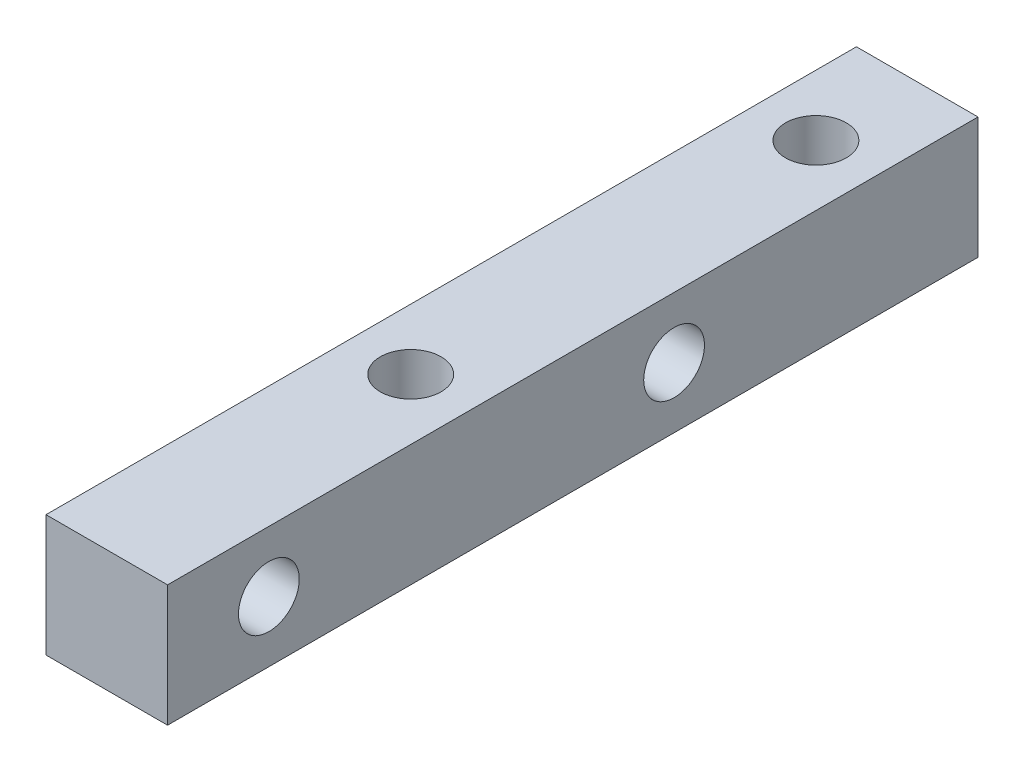
SolidWorks part; units mm, degrees
other "标注1"
sketch "草图4" plane through (6, 6, 0) normal (0.1455, 0.9686, -0.2015) x (-0.3057, 0.2377, 0.922)
material "6061-T6 (SS)"
ref_plane "前视基准面" through (0, 0, 0) normal (0, 0, 1) x (1, 0, 0)
ref_plane "上视基准面" through (0, 0, 0) normal (0, 1, 0) x (1, 0, 0)
ref_plane "右视基准面" through (0, 0, 0) normal (1, 0, 0) x (0, 0, -1)
sketch "草图1" plane through (0, 0, 0) normal (0, 0, 1) x (1, 0, 0)
  line L1 (0, 0) -> (6, 0)
  line L2 (0, 0) -> (0, 6)
  line L3 (0, 6) -> (6, 6)
  line L4 (6, 0) -> (6, 6)
  dimension "D1" = 6
  dimension "D2" = 6
extrude "凸台-拉伸1" add sketch "草图1" along normal blind 40
sketch "草图2" plane through (0, 6, 0) normal (0, 1, 0) x (1, 0, 0)
  line L0 (3, 0) -> (3, -5) construction
  line L1 (6, 0) -> (0, 0) construction
  line L2 (3, -5) -> (3, -25) construction
  circle A0 centre (3, -5) radius 1.5
  circle A1 centre (3, -25) radius 1.5
  dimension "D1" = 3
  dimension "D2" = 5
  dimension "D3" = 20
extrude "切除-拉伸1" cut sketch "草图2" against normal blind 50
cosmetic thread "装饰螺纹线5" parameters "D2"=3
cosmetic thread "装饰螺纹线6" parameters "D2"=3
sketch "草图3" plane through (0, 0, 0) normal (-1, 0, 0) x (0, 0, 1)
  line L0 (0, 3) -> (15, 3) construction
  line L1 (0, 6) -> (0, 0) construction
  line L2 (15, 3) -> (35, 3) construction
  circle A0 centre (35, 3) radius 1.5
  circle A1 centre (15, 3) radius 1.5
  dimension "D3" = 3
  dimension "D1" = 15
  dimension "D2" = 20
extrude "切除-拉伸2" cut sketch "草图3" against normal blind 50
cosmetic thread "装饰螺纹线7" parameters "D2"=3
cosmetic thread "装饰螺纹线8" parameters "D2"=3
move or copy body "实体-移动/复制1" [suppressed] bodies to move or copy 108 parameters "D1"=0, "D2"=0, "D3"=0
move or copy body "实体-移动/复制2" [suppressed] bodies to move or copy 109
